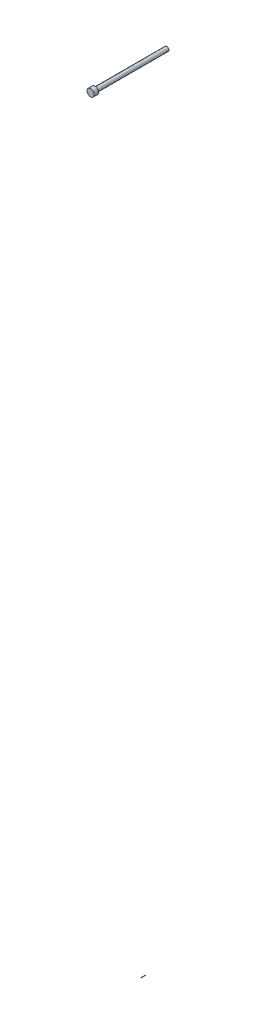
SolidWorks part; units mm, degrees
ref_plane "Front Plane" through (0, 0, 0) normal (0, 0, 1) x (1, 0, 0)
ref_plane "Top Plane" through (0, 0, 0) normal (0, 1, 0) x (1, 0, 0)
ref_plane "Right Plane" through (0, 0, 0) normal (1, 0, 0) x (0, 0, -1)
sketch "Sketch1" plane through (0, 0, 0) normal (0, 0, 1) x (1, 0, 0)
  circle A0 centre (35, 0) radius 0.0812
  circle A2 centre (0, 515.93) radius 2.5
extrude "Boss-Extrude1" add sketch "Sketch1" along normal blind 3
sketch "Sketch2" plane through (0, 0, 0) normal (0, 0, -1) x (-1, 0, 0)
  circle A1 centre (0, 515.93) radius 1.5
extrude "Boss-Extrude2" add sketch "Sketch2" along normal blind 50
